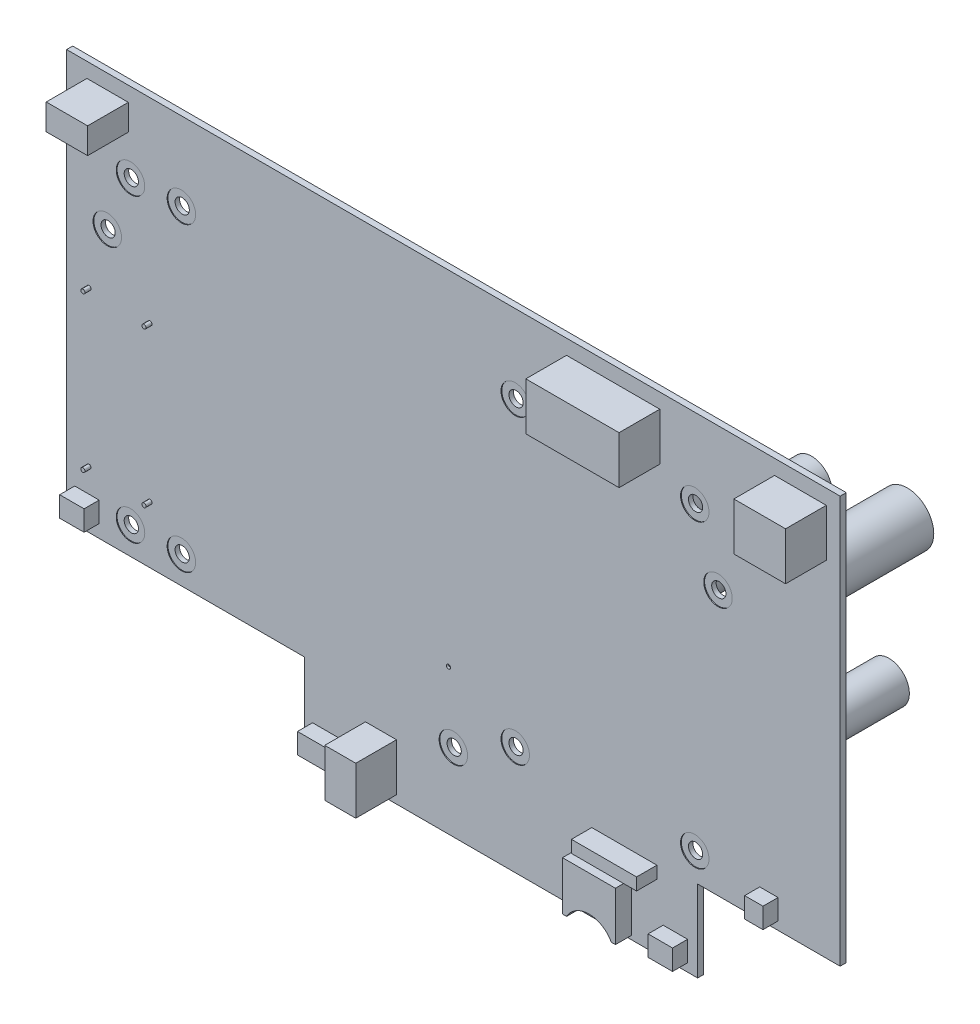
SolidWorks part; units mm, degrees
ref_plane "Face" through (0, 0, 0) normal (0, 0, 1) x (1, 0, 0)
ref_plane "Dessus" through (0, 0, 0) normal (0, 1, 0) x (1, 0, 0)
ref_plane "Droite" through (0, 0, 0) normal (1, 0, 0) x (0, 0, -1)
sketch "Esquisse1" plane through (0, 0, 0) normal (0, 0, 1) x (1, 0, 0)
  line L0 (87.1423, -46.9132) -> (87.1423, -26.9132)
  line L1 (87.1423, -26.9132) -> (122.1423, -26.9132)
  line L2 (122.1423, -26.9132) -> (122.1423, 73.0868)
  line L3 (122.1423, 73.0868) -> (-67.8577, 73.0868)
  line L4 (-67.8577, 73.0868) -> (-67.8577, -26.9132)
  line L5 (-67.8577, -26.9132) -> (-9.4458, -26.9132)
  line L6 (-9.4458, -26.9132) -> (-9.4458, -46.9132)
  line L7 (-9.4458, -46.9132) -> (87.1423, -46.9132)
extrude "Base-Extrusion" add sketch "Esquisse1" along normal blind 1.5
sketch "Esquisse2" plane through (0, 0, 0) normal (0, 0, -1) x (-1, 0, 0)
  circle A0 centre (-86.4423, 53.5868) radius 1.75
  circle A1 centre (52.1577, 53.5868) radius 1.75
  circle A2 centre (52.1577, -20.2132) radius 1.75
  circle A3 centre (-86.4423, -20.2132) radius 1.75
  dimension "D1" = 3.5
  dimension "D2" = 3.5
  dimension "D3" = 3.5
  dimension "D4" = 3.5
extrude "Enlèv. mat.-Extru.1" cut sketch "Esquisse2" against normal blind 2
sketch "Esquisse5" plane through (0, 0, 1.5) normal (0, 0, 1) x (1, 0, 0)
  line L0 (122.1423, -26.9132) -> (122.1423, 73.0868) construction
  line L1 (122.1423, 73.0868) -> (-67.8577, 73.0868) construction
  line L2 (27.1423, 73.0868) -> (27.1423, -57.4247) construction
  circle A0 centre (92.1423, 38.0868) radius 1.75
  circle A1 centre (-57.8577, 39.8368) radius 1.75
  circle A2 centre (27.1423, -27.9132) radius 1.75
  dimension "D1" = 30
  dimension "D3" = 3.5
  dimension "D4" = 66
  dimension "D5" = 3.5
  dimension "D6" = 3.5
  dimension "D2" = 35
extrude "Enlèv. mat.-Extru.2" cut sketch "Esquisse5" against normal blind 3
sketch "Esquisse6" plane through (0, 0, 0) normal (0, 0, -1) x (-1, 0, 0)
  circle A0 centre (-42.3423, 53.8141) radius 1.75
  circle A1 centre (39.6577, 53.8141) radius 1.75
  circle A2 centre (39.6577, -20.1859) radius 1.75
  circle A3 centre (-42.3423, -20.1859) radius 1.75
  dimension "D1" = 3.5
  dimension "D2" = 3.5
  dimension "D3" = 3.5
  dimension "D4" = 3.5
extrude "Enlèv. mat.-Extru.3" cut sketch "Esquisse6" against normal blind 2
sketch "Esquisse7" plane through (0, 0, 0) normal (0, 0, -1) x (-1, 0, 0)
  line L0 (-73.1423, 95.3031) -> (-73.1423, -81.5415) construction
  line L1 (-122.1423, -26.9132) -> (-122.1423, 73.0868) construction
  line L2 (-45.1037, 46.0868) -> (-133.1932, 46.0868) construction
  line L3 (-122.1423, 73.0868) -> (67.8577, 73.0868) construction
  line L4 (-42.9372, 29.0868) -> (-108.4753, 29.0868) construction
  circle A0 centre (-73.1423, 46.0868) radius 7.75
  circle A1 centre (-73.1423, 29.0868) radius 7.75
  dimension "D4" = 15.5
  dimension "D5" = 15.5
  dimension "D1" = 49
  dimension "D2" = 27
  dimension "D3" = 17
extrude "Boss.-Extru.1" add sketch "Esquisse7" along normal blind 14.5
sketch "Esquisse10" plane through (0, 0, 1.5) normal (0, 0, 1) x (1, 0, 0)
  circle A0 centre (25.9423, -11.2859) radius 0.5
extrude "Enlèv. mat.-Extru.4" cut sketch "Esquisse10" against normal blind 0.5
sketch "Esquisse11" plane through (0, 0, 1.5) normal (0, 0, 1) x (1, 0, 0)
  line L0 (-62.8577, 69.4368) -> (-52.6977, 69.4368)
  line L1 (-62.8577, 63.0868) -> (-52.6977, 63.0868)
  line L2 (-62.8577, 69.4368) -> (-62.8577, 63.0868)
  line L3 (-52.6977, 69.4368) -> (-52.6977, 63.0868)
  line L4 (122.1423, 73.0868) -> (-67.8577, 73.0868) construction
  line L5 (-67.8577, 73.0868) -> (-67.8577, -26.9132) construction
  line L6 (54.9423, 69.4368) -> (77.8423, 69.4368)
  line L7 (54.9423, 57.7368) -> (77.8423, 57.7368)
  line L8 (54.9423, 69.4368) -> (54.9423, 57.7368)
  line L9 (-9.4458, -26.9132) -> (-9.4458, -46.9132) construction
  line L10 (77.8423, 57.7368) -> (77.8423, 69.4368)
  line L11 (106.0423, 69.4368) -> (118.7423, 69.4368)
  line L12 (106.0423, 57.7368) -> (118.7423, 57.7368)
  line L13 (106.0423, 69.4368) -> (106.0423, 57.7368)
  line L14 (118.7423, 57.7368) -> (118.7423, 69.4368)
  line L20 (5.5542, -33.2132) -> (5.5542, -44.9132)
  line L21 (5.5542, -44.9132) -> (13.1742, -44.9132)
  line L22 (-9.4458, -46.9132) -> (87.1423, -46.9132) construction
  line L23 (5.5542, -33.2132) -> (13.1742, -33.2132)
  line L24 (13.1742, -44.9132) -> (13.1742, -33.2132)
  dimension "D1" = 6.35
  dimension "D2" = 10
  dimension "D3" = 5
  dimension "D4" = 10.16
  dimension "D5" = 15
  dimension "D7" = 22.9
  dimension "D6" = 12.7
  dimension "D10" = 2
  dimension "D11" = 11.7
  dimension "D12" = 7.62
extrude "Boss.-Extru.3" add sketch "Esquisse11" along normal blind 10
sketch "Esquisse12" plane through (0, 0, 0) normal (0, 0, -1) x (-1, 0, 0)
  line L0 (64.8577, 27.1458) -> (64.8577, -14.8542)
  line L1 (67.8577, 73.0868) -> (67.8577, -26.9132) construction
  line L2 (64.8577, -14.8542) -> (44.8577, -14.8542)
  line L3 (64.8577, 27.1458) -> (44.8577, 27.1458)
  line L4 (44.8577, 27.1458) -> (44.8577, -14.8542)
  dimension "D1" = 3
  dimension "D2" = 42
extrude "Boss.-Extru.4" add sketch "Esquisse12" along normal blind 12
sketch "Esquisse13" plane through (0, 0, -12) normal (0, 0, -1) x (-1, 0, 0)
  line L0 (64.8577, 27.1458) -> (44.8577, 27.1458) construction
  line L1 (64.8577, 27.1458) -> (44.8577, 27.1458)
  line L2 (64.8577, -14.8542) -> (64.8577, 27.1458) construction
  line L3 (64.8577, 17.1458) -> (64.8577, 27.1458)
  line L4 (44.8577, 27.1458) -> (44.8577, -14.8542) construction
  line L5 (44.8577, 27.1458) -> (44.8577, 17.1458)
  line L6 (64.8577, 17.1458) -> (44.8577, 17.1458)
  dimension "D1" = 10
extrude "Enlèv. mat.-Extru.5" cut sketch "Esquisse13" against normal blind 2
sketch "Esquisse14" plane through (0, 0, 1.5) normal (0, 0, 1) x (1, 0, 0)
  line L5 (102.3923, -24.9132) -> (106.8923, -24.9132)
  line L6 (78.6742, -44.9132) -> (84.6742, -44.9132)
  line L7 (78.6742, -39.9132) -> (78.6742, -44.9132)
  line L8 (78.6742, -39.9132) -> (84.6742, -39.9132)
  line L9 (84.6742, -39.9132) -> (84.6742, -44.9132)
  line L10 (-7.4458, -39.9132) -> (-7.4458, -44.9132)
  line L11 (0.0542, -39.9132) -> (0.0542, -44.9132)
  line L12 (-7.4458, -39.9132) -> (0.0542, -39.9132)
  line L13 (-7.4458, -44.9132) -> (0.0542, -44.9132)
  line L14 (-65.8577, -23.757) -> (-59.8577, -23.757)
  line L15 (-65.8577, -23.757) -> (-65.8577, -18.757)
  line L16 (-67.8577, 73.0868) -> (-67.8577, -26.9132) construction
  line L17 (-65.8577, -18.757) -> (-59.8577, -18.757)
  line L18 (-59.8577, -23.757) -> (-59.8577, -18.757)
  line L19 (102.3923, -19.9132) -> (102.3923, -24.9132)
  line L20 (102.3923, -19.9132) -> (106.8923, -19.9132)
  line L21 (106.8923, -19.9132) -> (106.8923, -24.9132)
  line L22 (-9.4458, -26.9132) -> (-9.4458, -46.9132) construction
  dimension "D6" = 2
  dimension "D1" = 6
  dimension "D2" = 2
  dimension "D7" = 6
  dimension "D5" = 7.5
extrude "Boss.-Extru.5" add sketch "Esquisse14" along normal blind 3.7
sketch "Esquisse15" plane through (0, 0, 1.5) normal (0, 0, 1) x (1, 0, 0)
  line L0 (57.9514, -45.9132) -> (58.9514, -45.9132)
  line L1 (-9.4458, -46.9132) -> (87.1423, -46.9132) construction
  line L2 (57.9514, -45.9132) -> (57.9514, -33.9132)
  line L3 (70.9514, -45.9132) -> (70.9514, -33.9132)
  line L4 (70.9514, -33.9132) -> (57.9514, -33.9132)
  line L8 (69.9514, -45.9132) -> (70.9514, -45.9132)
  arc A0 (69.9514, -45.9132) -> (58.9514, -45.9132) centre (64.4514, -48.9122) ccw
  dimension "D1" = 1
  dimension "D2" = 13
extrude "Boss.-Extru.6" add sketch "Esquisse15" along normal blind 4
sketch "Esquisse16" plane through (0, 0, 1.5) normal (0, 0, 1) x (1, 0, 0)
  line L0 (61.1423, -30.9132) -> (77.1423, -30.9132)
  line L1 (77.1423, -30.9132) -> (77.1423, -27.9132)
  line L2 (61.1423, -30.9132) -> (61.1423, -27.9132)
  line L3 (61.1423, -27.9132) -> (77.1423, -27.9132)
  line L4 (87.1423, -46.9132) -> (87.1423, -26.9132) construction
  line L5 (-9.4458, -46.9132) -> (87.1423, -46.9132) construction
  dimension "D1" = 16
  dimension "D2" = 10
  dimension "D3" = 3
  dimension "D4" = 16
extrude "Boss.-Extru.7" add sketch "Esquisse16" along normal blind 5
sketch "Esquisse17" plane through (0, 0, 0) normal (0, 0, -1) x (-1, 0, 0)
  circle A0 centre (-27.1423, -24.4132) radius 8
  circle A1 centre (-92.1423, 41.5868) radius 8
  circle A2 centre (57.8577, 43.3368) radius 8
extrude "Enlèv. mat.-Extru.6" cut sketch "Esquisse17" against normal blind 0.2
sketch "Esquisse18" plane through (0, 0, 0) normal (0, 0, -1) x (-1, 0, 0)
  circle A0 centre (-86.4423, 53.5868) radius 3.5
  circle A1 centre (-42.3423, 53.8141) radius 3.5
  circle A2 centre (39.6577, 53.8141) radius 3.5
  circle A3 centre (52.1577, 53.5868) radius 3.5
  circle A4 centre (52.1577, -20.2132) radius 3.5
  circle A5 centre (39.6577, -20.1859) radius 3.5
  circle A6 centre (-42.3423, -20.1859) radius 3.5
  circle A7 centre (-86.4423, -20.2132) radius 3.5
extrude "Enlèv. mat.-Extru.7" cut sketch "Esquisse18" against normal blind 0.2
sketch "Esquisse19" plane through (0, 0, 1.5) normal (0, 0, 1) x (1, 0, 0)
  circle A0 centre (-52.1577, 53.5868) radius 3.5
  circle A1 centre (-39.6577, 53.8141) radius 3.5
  circle A2 centre (42.3423, 53.8141) radius 3.5
  circle A3 centre (86.4423, 53.5868) radius 3.5
  circle A4 centre (92.1423, 38.0868) radius 3.5
  circle A5 centre (86.4423, -20.2132) radius 3.5
  circle A6 centre (42.3423, -20.1859) radius 3.5
  circle A7 centre (27.1423, -27.9132) radius 3.5
  circle A8 centre (-39.6577, -20.1859) radius 3.5
  circle A9 centre (-52.1577, -20.2132) radius 3.5
  circle A10 centre (-57.8577, 39.8368) radius 3.5
extrude "Enlèv. mat.-Extru.8" cut sketch "Esquisse19" against normal blind 0.2
sketch "Esquisse21" plane through (0, 0, 0) normal (0, 0, -1) x (-1, 0, 0)
  line L0 (-122.1423, -26.9132) -> (-122.1423, 73.0868) construction
  line L1 (-122.1423, 73.0868) -> (67.8577, 73.0868) construction
  circle A0 centre (-107.1423, 45.0868) radius 6.5
  dimension "D1" = 15
  dimension "D2" = 28
extrude "Extrusion1" add sketch "Esquisse21" along normal blind 30
sketch "Esquisse22" plane through (0, 0, 0) normal (0, 0, -1) x (-1, 0, 0)
  line L0 (-122.1423, -26.9132) -> (-122.1423, 73.0868) construction
  line L1 (-122.1423, 73.0868) -> (67.8577, 73.0868) construction
  circle A0 centre (-100.6423, 58.5868) radius 5
  dimension "D1" = 21.5
  dimension "D2" = 14.5
extrude "Extrusion2" add sketch "Esquisse22" along normal blind 13
sketch "Esquisse23" plane through (0, 0, 0) normal (0, 0, -1) x (-1, 0, 0)
  line L0 (-122.1423, 73.0868) -> (67.8577, 73.0868) construction
  line L1 (-122.1423, -26.9132) -> (-122.1423, 73.0868) construction
  circle A0 centre (-116.1423, 21.5868) radius 5
  dimension "D1" = 51.5
  dimension "D2" = 6
extrude "Extrusion3" add sketch "Esquisse23" along normal blind 16.5
sketch "Esquisse24" plane through (0, 0, 0) normal (0, 0, -1) x (-1, 0, 0)
  line L0 (-122.1423, 73.0868) -> (67.8577, 73.0868) construction
  line L1 (-122.1423, -26.9132) -> (-122.1423, 73.0868) construction
  circle A0 centre (-93.1423, 18.0868) radius 10.5
  dimension "D1" = 55
  dimension "D2" = 29
extrude "Extrusion4" add sketch "Esquisse24" along normal blind 7.5
sketch "Esquisse25" plane through (-64.8577, 0, 0) normal (-1, 0, 0) x (0, 0, 1)
  line L0 (-12, -14.8542) -> (0, -14.8542) construction
  line L1 (0, 27.1458) -> (-2, 27.1458)
  line L2 (0, 27.1458) -> (0, -14.8542)
  line L3 (0, -14.8542) -> (-2, -14.8542)
  line L4 (-2, 27.1458) -> (-2, -14.8542)
  dimension "D1" = 2
extrude "Enlèv. mat.-Extru.9" cut sketch "Esquisse25" against normal up to vertex
sketch "Esquisse26" plane through (-64.8577, 0, 0) normal (-1, 0, 0) x (0, 0, 1)
  line L0 (-10, 27.1458) -> (-2, 27.1458) construction
  line L1 (-2.8, 27.1458) -> (-3.8, 27.1458)
  line L2 (-2.8, 27.1458) -> (-2.8, -14.8542)
  line L3 (-2.8, -14.8542) -> (-3.8, -14.8542)
  line L4 (-3.8, 27.1458) -> (-3.8, -14.8542)
  line L5 (-12, -14.8542) -> (-2, -14.8542) construction
  line L6 (-2, 27.1458) -> (-2, -14.8542) construction
  dimension "D1" = 0.8
  dimension "D2" = 1
extrude "Enlèv. mat.-Extru.10" cut sketch "Esquisse26" against normal up to vertex
sketch "Esquisse27" plane through (0, 0, -2.8) normal (0, 0, -1) x (-1, 0, 0)
  line L0 (54.8577, 32.4182) -> (54.8577, -16.8141) construction
  line L4 (39.827, 6.1458) -> (70.4892, 6.1458) construction
  circle A0 centre (47.3577, 25.1458) radius 0.5
  circle A1 centre (62.3577, 25.1458) radius 0.5
  circle A2 centre (62.3577, -12.8542) radius 0.5
  circle A3 centre (47.3577, -12.8542) radius 0.5
  dimension "D1" = 19
  dimension "D2" = 7.5
extrude "Extrusion5" add sketch "Esquisse27" against normal blind 5.8
sketch "Esquisse28" plane through (0, 0, -3.8) normal (0, 0, 1) x (1, 0, 0)
  line L0 (-54.8577, 31.2033) -> (-54.8577, -16.4624) construction
  circle A0 centre (-59.8577, 11.6526) radius 0.3
  circle A1 centre (-59.8577, 1.6526) radius 0.3
  circle A2 centre (-49.8577, 1.6526) radius 0.3
  circle A3 centre (-49.8577, 11.6526) radius 0.3
  circle A4 centre (-59.9048, -5.1775) radius 0.3
  circle A5 centre (-59.9048, -7.1775) radius 0.3
  circle A6 centre (-59.9048, -9.1775) radius 0.3
  circle A7 centre (-52.2281, 22.1173) radius 0.3
  circle A8 centre (-52.2281, 19.4063) radius 0.3
  circle A9 centre (-57.4873, 19.4063) radius 0.3
  circle A10 centre (-57.4873, 22.1173) radius 0.3
  dimension "D1" = 10
  dimension "D2" = 2
  dimension "D3" = 2
extrude "Extrusion6" add sketch "Esquisse28" along normal blind 2.8
